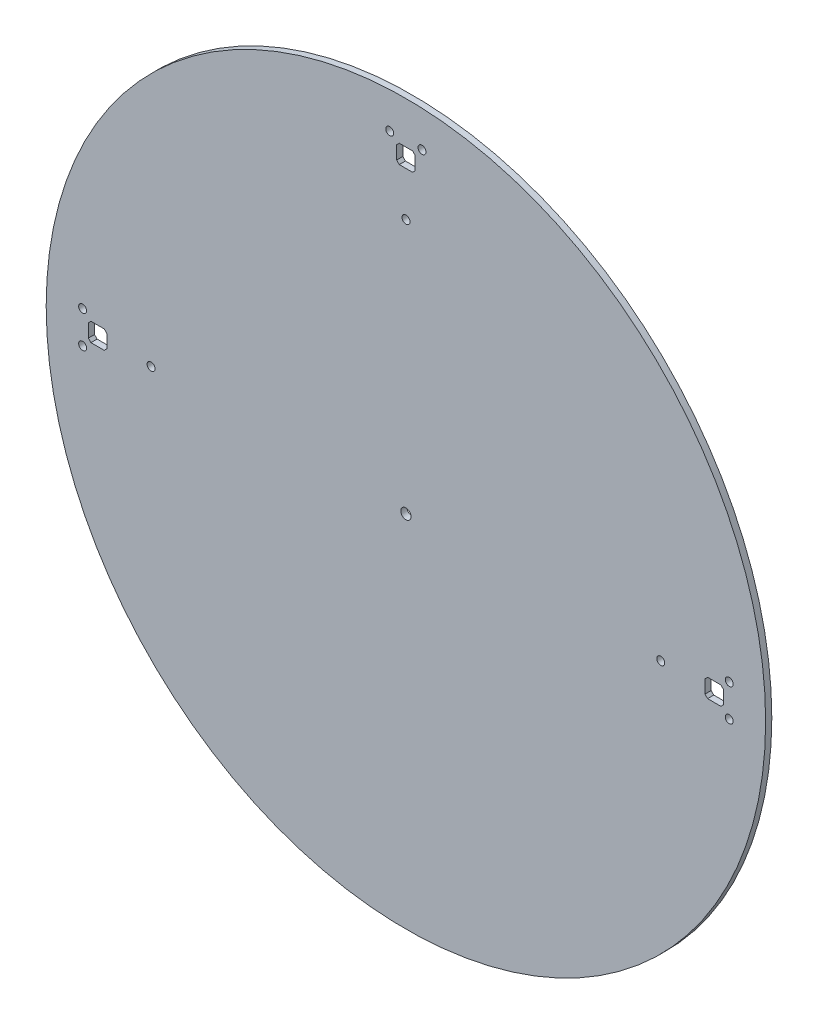
SolidWorks part; units mm, degrees
ref_plane "Front Plane" through (0, 0, 0) normal (0, 0, 1) x (1, 0, 0)
ref_plane "Top Plane" through (0, 0, 0) normal (0, 1, 0) x (1, 0, 0)
ref_plane "Right Plane" through (0, 0, 0) normal (1, 0, 0) x (0, 0, -1)
sketch "Sketch1" plane through (0, 0, 0) normal (0, 0, 1) x (1, 0, 0)
  line L0 (-300, 0) -> (300, 0) construction
  line L1 (0, 0) -> (0, 300) construction
  line L2 (9.0006, 306.4495) -> (9.0006, 293.5295)
  line L3 (9.0006, 293.5295) -> (6.4606, 290.9895)
  line L4 (6.4606, 290.9895) -> (-6.4594, 290.9895)
  line L5 (-6.4594, 290.9895) -> (-8.9994, 293.5295)
  line L6 (-8.9994, 293.5295) -> (-8.9994, 306.4495)
  line L7 (-8.9994, 306.4495) -> (-6.4594, 308.9895)
  line L8 (-6.4594, 308.9895) -> (6.4606, 308.9895)
  line L9 (6.4606, 308.9895) -> (9.0006, 306.4495)
  line L10 (9.0006, 290.9895) -> (-8.9994, 308.9895) construction
  line L15 (-8.9994, 290.9895) -> (9.0006, 308.9895) construction
  line L16 (0.1003, 247.9365) -> (-15.7509, 314.5497) construction
  line L17 (15.6504, 314.5486) -> (-15.7509, 314.5497) construction
  line L18 (0.1003, 247.9365) -> (15.6504, 314.5486) construction
  line L19 (-306.4472, 8.9714) -> (-293.5272, 8.9714)
  line L20 (-293.5272, 8.9714) -> (-290.9872, 6.4314)
  line L21 (-290.9872, 6.4314) -> (-290.9872, -6.4886)
  line L22 (-290.9872, -6.4886) -> (-293.5272, -9.0286)
  line L23 (-293.5272, -9.0286) -> (-306.4472, -9.0286)
  line L24 (-306.4472, -9.0286) -> (-308.9872, -6.4886)
  line L25 (-308.9872, -6.4886) -> (-308.9872, 6.4314)
  line L26 (-308.9872, 6.4314) -> (-306.4472, 8.9714)
  line L27 (-290.9872, 8.9714) -> (-308.9872, -9.0286) construction
  line L32 (-290.9872, -9.0286) -> (-308.9872, 8.9714) construction
  line L33 (-247.9343, 0.0711) -> (-314.5475, -15.7801) construction
  line L34 (-314.5464, 15.6212) -> (-314.5475, -15.7801) construction
  line L35 (-247.9343, 0.0711) -> (-314.5464, 15.6212) construction
  line L54 (247.9269, 0.0992) -> (314.539, 15.6492) construction
  line L55 (314.539, 15.6492) -> (314.5401, -15.752) construction
  line L56 (247.9269, 0.0992) -> (314.5401, -15.752) construction
  line L57 (290.9798, -9.0005) -> (308.9798, 8.9995) construction
  line L62 (290.9798, 8.9995) -> (308.9798, -9.0005) construction
  line L63 (308.9798, 6.4595) -> (306.4398, 8.9995)
  line L64 (308.9798, -6.4605) -> (308.9798, 6.4595)
  line L65 (306.4398, -9.0005) -> (308.9798, -6.4605)
  line L66 (293.5198, -9.0005) -> (306.4398, -9.0005)
  line L67 (290.9798, -6.4605) -> (293.5198, -9.0005)
  line L68 (290.9798, 6.4595) -> (290.9798, -6.4605)
  line L69 (293.5198, 8.9995) -> (290.9798, 6.4595)
  line L70 (306.4398, 8.9995) -> (293.5198, 8.9995)
  circle A0 centre (0, 0) radius 300 construction
  circle A1 centre (0.1003, 247.9365) radius 0.1979
  circle A2 centre (-15.7509, 314.5497) radius 0.1981
  circle A3 centre (15.6504, 314.5486) radius 0.1999
  circle A4 centre (-15.7509, 314.5497) radius 3.8536
  circle A5 centre (15.6504, 314.5486) radius 3.8536
  circle A6 centre (0.1003, 247.9365) radius 3.8536
  circle A7 centre (0.0006, 299.9895) radius 3.177 construction
  circle A8 centre (-247.9343, 0.0711) radius 0.1979
  circle A9 centre (-314.5475, -15.7801) radius 0.1981
  circle A10 centre (-314.5464, 15.6212) radius 0.1999
  circle A11 centre (-314.5475, -15.7801) radius 3.8536
  circle A12 centre (-314.5464, 15.6212) radius 3.8536
  circle A13 centre (-247.9343, 0.0711) radius 3.8536
  circle A14 centre (-299.9872, -0.0286) radius 3.177 construction
  circle A22 centre (299.9798, -0.0005) radius 3.177 construction
  circle A23 centre (247.9269, 0.0992) radius 3.8536
  circle A24 centre (314.539, 15.6492) radius 3.8536
  circle A25 centre (314.5401, -15.752) radius 3.8536
  circle A26 centre (314.539, 15.6492) radius 0.1999
  circle A27 centre (314.5401, -15.752) radius 0.1981
  circle A28 centre (247.9269, 0.0992) radius 0.1979
  circle A29 centre (0, 0) radius 350
extrude "Boss-Extrude1" add sketch "Sketch1" along normal blind 6 contours A6 | A5 | A4 | L8 L9 L2 L3 L4 L5 L6 L7 | A11 | A13 | L25 L26 L19 L20 L21 L22 L23 L24 | A12 | A29 | A25 | A23 | L70 L69 L68 L67 L66 L65 L64 L63 | A24
sketch "Sketch3" plane through (0, 0, 6) normal (0, 0, 1) x (1, 0, 0)
  circle A0 centre (0, 0) radius 5
extrude "Cut-Extrude1" cut sketch "Sketch3" against normal blind 23 contours A0
